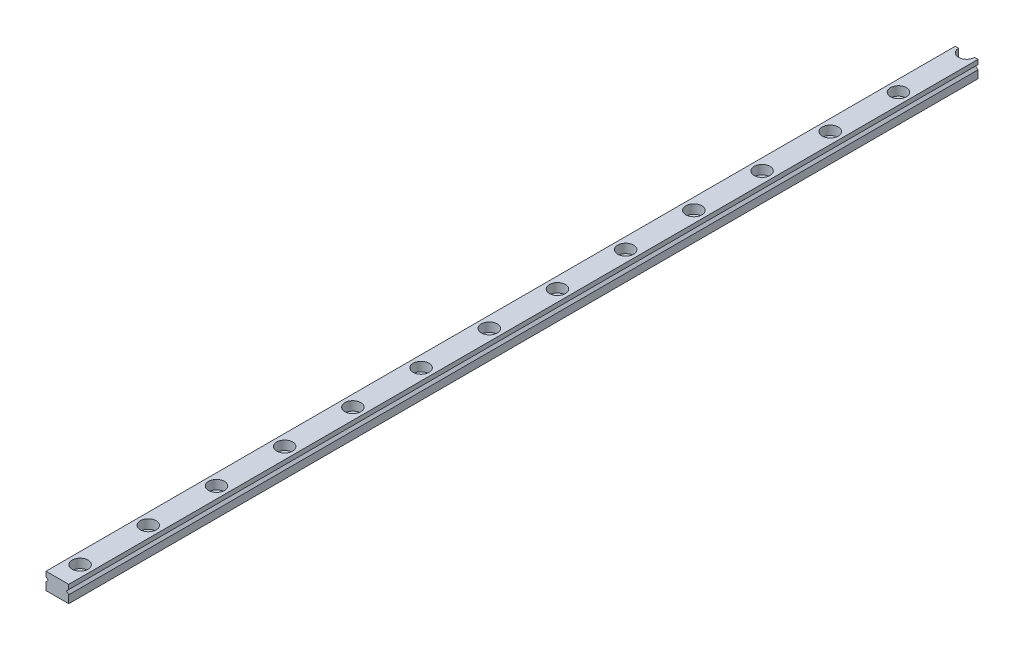
SolidWorks part; units mm, degrees
material "AISI 304"
ref_plane "前视基准面" through (0, 0, 0) normal (0, 0, 1) x (1, 0, 0)
ref_plane "上视基准面" through (0, 0, 0) normal (0, 1, 0) x (1, 0, 0)
ref_plane "右视基准面" through (0, 0, 0) normal (1, 0, 0) x (0, 0, -1)
sketch "Sketch1" plane through (0, 0, 0) normal (0, 0, 1) x (1, 0, 0)
  line L0 (0, 0) -> (0, 3.7)
  line L1 (0, 3.7) -> (5, 3.7)
  line L2 (5, 3.7) -> (5, 0)
  line L3 (5, 0) -> (0, 0)
  dimension "D1" = 3.7
  dimension "D2" = 5
extrude "Boss-Extrude1" add sketch "Sketch1" against normal blind 400
sketch "Sketch2" plane through (0, 3.7, 0) normal (0, 1, 0) x (1, 0, 0)
  line L0 (2.5, -0.9977) -> (2.5, 11.7262) construction
  line L1 (-6.0403, 5) -> (12.1202, 5) construction
  line L2 (5, 0) -> (0, 0) construction
  line L3 (5, 400) -> (5, 0) construction
  circle A0 centre (2.5, 5) radius 1.75
  circle A1 centre (2.5, 20) radius 1.75
  circle A2 centre (2.5, 35) radius 1.75
  circle A3 centre (2.5, 50) radius 1.75
  circle A4 centre (2.5, 65) radius 1.75
  circle A5 centre (2.5, 80) radius 1.75
  circle A6 centre (2.5, 95) radius 1.75
  circle A7 centre (2.5, 110) radius 1.75
  circle A8 centre (2.5, 125) radius 1.75
  circle A9 centre (2.5, 140) radius 1.75
  circle A10 centre (2.5, 155) radius 1.75
  circle A11 centre (2.5, 170) radius 1.75
  circle A12 centre (2.5, 185) radius 1.75
  circle A13 centre (2.5, 200) radius 1.75
  circle A14 centre (2.5, 215) radius 1.75
  circle A15 centre (2.5, 230) radius 1.75
  circle A16 centre (2.5, 245) radius 1.75
  circle A17 centre (2.5, 260) radius 1.75
  circle A18 centre (2.5, 275) radius 1.75
  circle A19 centre (2.5, 290) radius 1.75
  circle A20 centre (2.5, 305) radius 1.75
  circle A21 centre (2.5, 320) radius 1.75
  circle A22 centre (2.5, 335) radius 1.75
  circle A23 centre (2.5, 350) radius 1.75
  circle A24 centre (2.5, 365) radius 1.75
  circle A25 centre (2.5, 380) radius 1.75
  circle A26 centre (2.5, 395) radius 1.75
  dimension "D3" = 3.5
  dimension "D1" = 5
  dimension "D2" = 2.5
  dimension "D5" = 390
  dimension "D4" = 27
extrude "Cut-Extrude1" cut sketch "Sketch2" against normal blind 2
sketch "Sketch3" plane through (0, 1.7, 0) normal (0, 1, 0) x (1, 0, 0)
  circle A0 centre (2.5, 5) radius 1
  circle A1 centre (2.5, 20) radius 1
  circle A2 centre (2.5, 35) radius 1
  circle A3 centre (2.5, 50) radius 1
  circle A4 centre (2.5, 65) radius 1
  circle A5 centre (2.5, 80) radius 1
  circle A6 centre (2.5, 95) radius 1
  circle A7 centre (2.5, 110) radius 1
  circle A8 centre (2.5, 125) radius 1
  circle A9 centre (2.5, 140) radius 1
  circle A10 centre (2.5, 155) radius 1
  circle A11 centre (2.5, 170) radius 1
  circle A12 centre (2.5, 185) radius 1
  circle A13 centre (2.5, 200) radius 1
  circle A14 centre (2.5, 215) radius 1
  circle A15 centre (2.5, 230) radius 1
  circle A16 centre (2.5, 245) radius 1
  circle A17 centre (2.5, 260) radius 1
  circle A18 centre (2.5, 275) radius 1
  circle A19 centre (2.5, 290) radius 1
  circle A20 centre (2.5, 305) radius 1
  circle A21 centre (2.5, 320) radius 1
  circle A22 centre (2.5, 335) radius 1
  circle A23 centre (2.5, 350) radius 1
  circle A24 centre (2.5, 365) radius 1
  circle A25 centre (2.5, 380) radius 1
  circle A26 centre (2.5, 395) radius 1
  dimension "D1" = 2
  dimension "D3" = 390
  dimension "D2" = 27
extrude "Cut-Extrude2" cut sketch "Sketch3" against normal through all
sketch "Sketch4" plane through (0, 0, 0) normal (0, 0, 1) x (1, 0, 0)
  line L0 (2.5, 3.8064) -> (2.5, -0.1865) construction
  line L1 (5, 0) -> (5, 3.7) construction
  line L2 (0, 2.7) -> (0.5, 2.2)
  line L3 (0, 3.7) -> (0, 0) construction
  line L4 (0.5, 2.2) -> (0, 1.7)
  line L5 (0, 2.7) -> (0, 1.7)
  line L6 (5, 2.7) -> (4.5, 2.2)
  line L7 (4.5, 2.2) -> (5, 1.7)
  line L8 (5, 2.7) -> (5, 1.7)
  dimension "D1" = 2.5
  dimension "D2" = 45
  dimension "D3" = 45
  dimension "D4" = 1
  dimension "D5" = 0.5
extrude "Cut-Extrude3" cut sketch "Sketch4" against normal through all
sketch "Sketch5" plane through (0, 0, -400) normal (0, 0, -1) x (-1, 0, 0)
  line L0 (-7.5909, 5.5914) -> (-7.5909, -0.9609)
  line L1 (-7.5909, -0.9609) -> (2.7347, -0.9609)
  line L2 (2.7347, -0.9609) -> (2.7347, 5.5914)
  line L3 (2.7347, 5.5914) -> (-7.5909, 5.5914)
extrude "Cut-Extrude4" cut sketch "Sketch5" against normal blind 200
